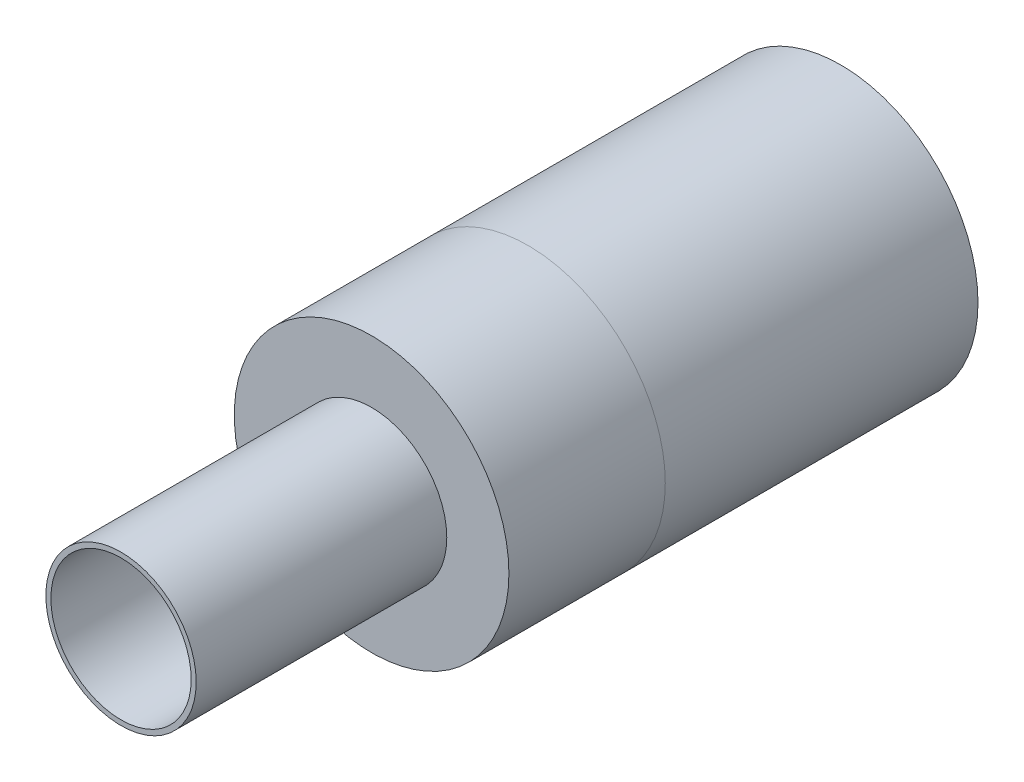
SolidWorks part; units mm, degrees
material "6061-T6 (SS)"
ref_plane "X-Y Datum" through (0, 0, 0) normal (0, 0, 1) x (1, 0, 0)
ref_plane "X-Z Datum" through (0, 0, 0) normal (0, 1, 0) x (1, 0, 0)
ref_plane "Y-Z Datum" through (0, 0, 0) normal (1, 0, 0) x (0, 0, -1)
sketch "Sketch1" plane through (0, 0, 0) normal (0, 0, 1) x (1, 0, 0)
  circle A0 centre (0, 0) radius 17.399
  dimension "D1" = 34.798
extrude "Boss-Extrude1" add sketch "Sketch1" along normal blind 59.436
sketch "Sketch2" plane through (0, 0, 59.436) normal (0, 0, 1) x (1, 0, 0)
  circle A0 centre (0, 0) radius 9.525
  dimension "D1" = 19.05
extrude "Boss-Extrude2" add sketch "Sketch2" along normal blind 31.75
sketch "Sketch5" plane through (0, 0, 0) normal (0, 0, -1) x (-1, 0, 0)
  circle A0 centre (0, 0) radius 8.89
  dimension "D1" = 17.78
extrude "Cut-Extrude1" cut sketch "Sketch5" against normal up to surface (91.186 mm away) up to face at (9.525, 0, 91.186)
ref_plane "Plane1" through (0, 0, 39.624) normal (0, 0, 1) x (1, 0, 0)
split line "Split Line1"
